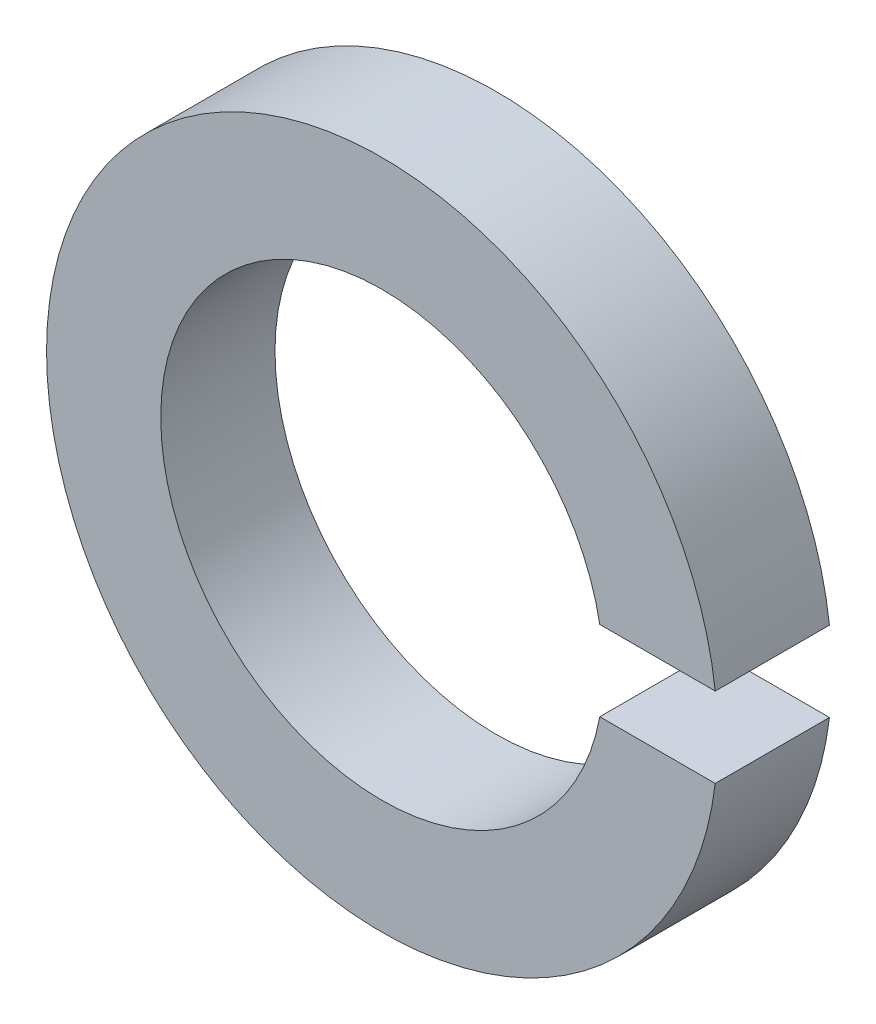
SolidWorks part; units mm, degrees
ref_plane "Спереди" through (0, 0, 0) normal (0, 0, 1) x (1, 0, 0)
ref_plane "Сверху" through (0, 0, 0) normal (0, 1, 0) x (1, 0, 0)
ref_plane "Справа" through (0, 0, 0) normal (1, 0, 0) x (0, 0, -1)
sketch "Эскиз1" plane through (0, 0, 0) normal (0, 0, 1) x (1, 0, 0)
  circle A0 centre (0, 0) radius 2.35
  circle A1 centre (0, 0) radius 1.55
  dimension "D1" = 4.7
  dimension "D2" = 3.1
extrude "Вытянуть1" add sketch "Эскиз1" along normal blind 0.8
sketch "Эскиз2" plane through (0, 0, 0.8) normal (0, 0, 1) x (1, 0, 0)
  line L0 (0, 0) -> (0.123, 0) construction
  line L1 (2.35, 0) -> (-2.35, 0) construction
  line L3 (1.5063, 0.28) -> (2.4373, 0.28)
  line L4 (1.5063, 0.28) -> (1.5063, -0.28)
  line L5 (1.5063, -0.28) -> (2.4373, -0.28)
  line L6 (2.4373, 0.28) -> (2.4373, -0.28)
  circle A0 centre (0, 0) radius 2.35 construction
  dimension "D1" = 0.28
  dimension "D2" = 0.56
extrude "Вырез-Вытянуть1" cut sketch "Эскиз2" against normal through all
